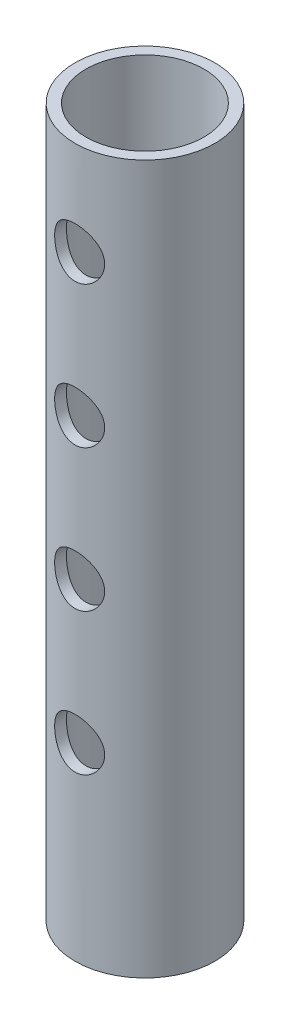
SolidWorks part; units mm, degrees
material "ABS"
ref_plane "前视基准面" through (0, 0, 0) normal (0, 0, 1) x (1, 0, 0)
ref_plane "上视基准面" through (0, 0, 0) normal (0, 1, 0) x (1, 0, 0)
ref_plane "右视基准面" through (0, 0, 0) normal (1, 0, 0) x (0, 0, -1)
other "Configuration Table"
sketch "草图1" plane through (0, 0, 0) normal (0, 1, 0) x (1, 0, 0)
  circle A0 centre (0, 0) radius 6.25
  circle A1 centre (0, 0) radius 7.4
  dimension "D1" = 12.5
  dimension "D2" = 14.8
extrude "凸台-拉伸1" add sketch "草图1" along normal blind 75 contours A1 A0
sketch "草图3" plane through (0, 0, 0) normal (0, 0, 1) x (1, 0, 0)
  circle A0 centre (0, 20) radius 2.65 construction
  circle A1 centre (0, 35) radius 2.65 construction
  circle A2 centre (0, 50) radius 2.65 construction
  circle A3 centre (0, 65) radius 2.65 construction
  circle A4 centre (0, 20) radius 2.65
  circle A5 centre (0, 35) radius 2.65
  circle A6 centre (0, 50) radius 2.65
  circle A7 centre (0, 65) radius 2.65
extrude "切除-拉伸1" cut sketch "草图3" against normal through all and the other way through all
